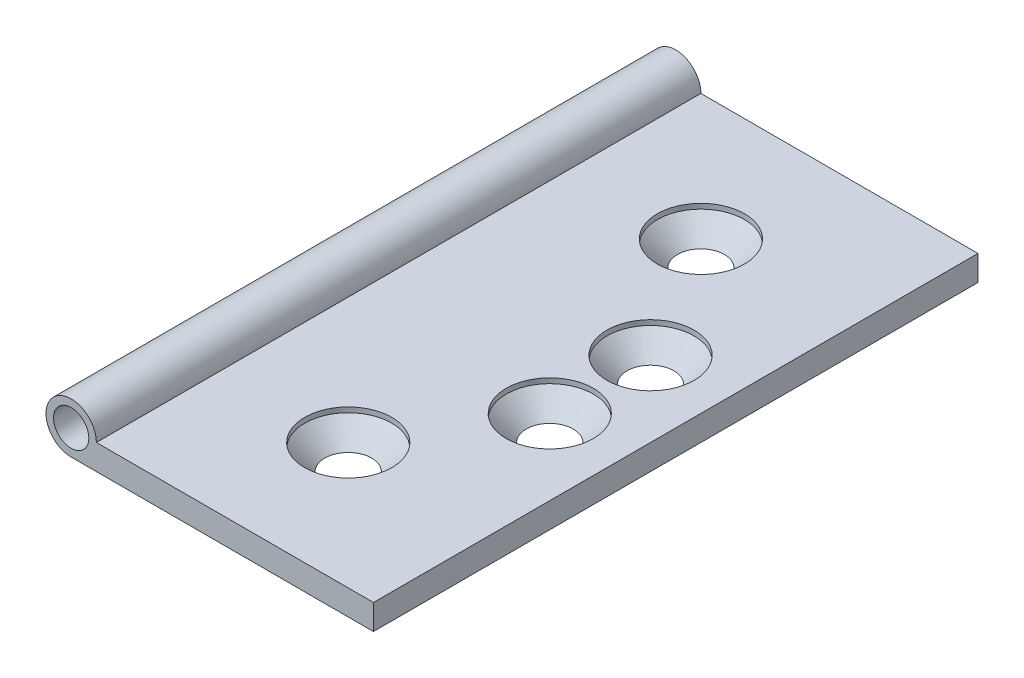
SolidWorks part; units mm, degrees
ref_plane "Спереди" through (0, 0, 0) normal (0, 0, 1) x (1, 0, 0)
ref_plane "Сверху" through (0, 0, 0) normal (0, 1, 0) x (1, 0, 0)
ref_plane "Справа" through (0, 0, 0) normal (1, 0, 0) x (0, 0, -1)
other "Configuration Table"
sketch "Эскиз1" plane through (0, 0, 0) normal (0, 0, 1) x (1, 0, 0)
  line L0 (0, 0) -> (60, 0)
extrude "Вытянуть-Тонкостенный1" add sketch "Эскиз1" along normal mid plane 120 thin
sketch "Эскиз3" plane through (0, 0, 60) normal (0, 0, 1) x (1, 0, 0)
  circle A0 centre (0, 0) radius 5
extrude "Бобышка-Вытянуть1" add sketch "Эскиз3" against normal blind 120
sketch "Эскиз4" plane through (0, 0, 60) normal (0, 0, 1) x (1, 0, 0)
  circle A0 centre (0, 0) radius 3.5
extrude "Вырез-Вытянуть1" cut sketch "Эскиз4" against normal blind 120 contours A0
sketch "Эскиз7" plane through (0, 0, 0) normal (0, 1, 0) x (1, 0, 0)
  point P0 (30, -35)
  point P2 (45, -10)
  point P9 (23.1712, -56.9704)
  dimension "D1" = 25
  dimension "D2" = 30
  dimension "D3" = 25
  dimension "D4" = 15
hole_wizard "Зенковка для  винта с полупотайной головкой M81" positions "Эскиз7" profile "Эскиз6" countersink size "M8" standard "Ansi Metric" end condition through all
sketch "Эскиз6" plane through (30, 0, 35) normal (1, 0, 0) x (0, 0, 1)
  line L0 (0, 0) -> (0, 5)
  line L1 (0, 5) -> (4.5, 5)
  line L2 (4.5, 5) -> (4.5, 5.15)
  line L3 (4.5, 5.15) -> (8.65, 1)
  line L4 (8.65, 1) -> (8.65, 0)
  line L6 (8.65, 0) -> (0, 0)
  line L7 (-4.5, 5.15) -> (-8.65, 1) construction
  line L11 (0, -6.35) -> (0, 107.95) construction
  dimension "Диаметр сквозного отверстия" = 9
  dimension "Глубина сквозного отверстия" = 5
  dimension "Диаметр зенковки" = 17.3
  dimension "Угол зенковки" = 90
  dimension "Утопленность" = 1
mirror "Зеркальное отражение2" about plane through (0, 0, 0) normal (0, 0, 1) of "Зенковка для  винта с полупотайной головкой M81"
equation "\"D2@Эскиз7\"= 60мм / 2"
equation "\"D3@Эскиз7\"= 75мм / 3"
